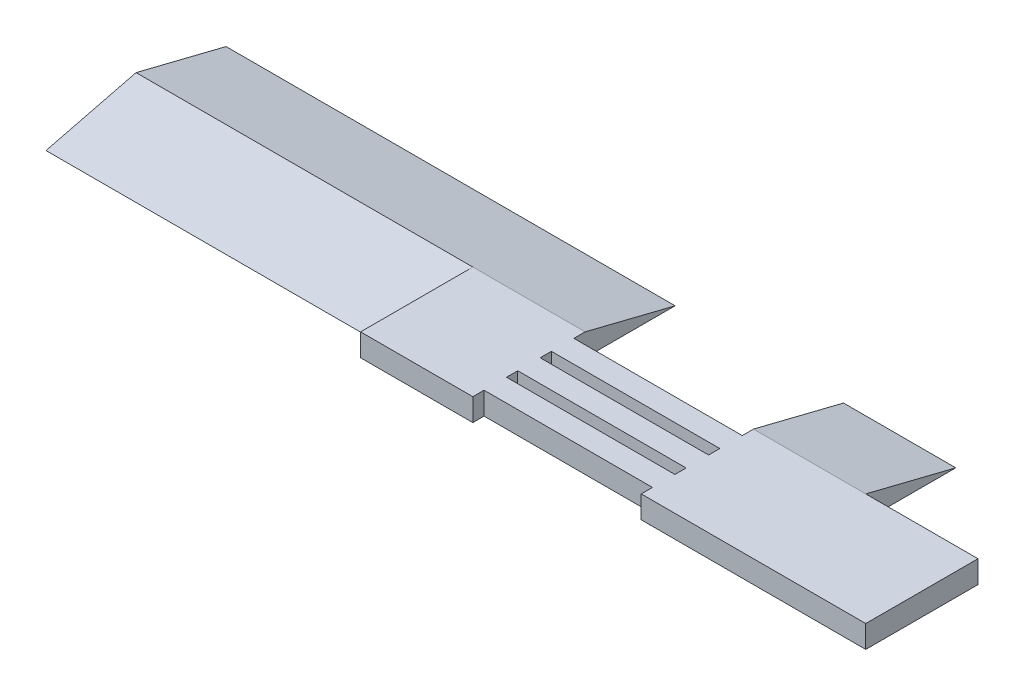
SolidWorks part; units mm, degrees
ref_plane "前视基准面" through (0, 0, 0) normal (0, 0, 1) x (1, 0, 0)
ref_plane "上视基准面" through (0, 0, 0) normal (0, 1, 0) x (1, 0, 0)
ref_plane "右视基准面" through (0, 0, 0) normal (1, 0, 0) x (0, 0, -1)
sketch "草图1" plane through (0, 0, 0) normal (0, 1, 0) x (1, 0, 0)
  line L1 (0, 0) -> (2000, 0)
  line L2 (0, 0) -> (0, 1000)
  line L3 (0, 1000) -> (2000, 1000)
  line L4 (2000, 0) -> (2000, 1000)
  dimension "D1" = 2000
  dimension "D2" = 1000
extrude "凸台-拉伸1" add sketch "草图1" along normal blind 200
sketch "草图2" plane through (0, 0, 0) normal (-1, 0, 0) x (0, 0, 1)
  line L0 (-1000, 200) -> (-1802.1562, 0)
  line L1 (-1000, 200) -> (-1000, 0) construction
  line L2 (-1000, 0) -> (-1802.1562, 0)
  line L3 (-1000, 200) -> (-1000, 0)
  dimension "D1" = 76
extrude "凸台-拉伸2" add sketch "草图2" against normal blind 1000
sketch "草图3" plane through (0, 0, 0) normal (-1, 0, 0) x (0, 0, 1)
  line L0 (-1000, 200) -> (0, 200) construction
  line L1 (-100, 200) -> (-300, 200)
  line L2 (-100, 200) -> (-100, 0)
  line L3 (-100, 0) -> (-300, 0)
  line L4 (-300, 200) -> (-300, 0)
  line L5 (-1802.1562, 0) -> (0, 0) construction
  line L6 (0, 200) -> (0, 0) construction
  line L7 (-400, 200) -> (-600, 200)
  line L8 (-400, 200) -> (-400, 0)
  line L9 (-400, 0) -> (-600, 0)
  line L10 (-600, 200) -> (-600, 0)
  line L11 (-700, 200) -> (-900, 200)
  line L12 (-700, 200) -> (-700, 0)
  line L13 (-700, 0) -> (-900, 0)
  line L14 (-900, 200) -> (-900, 0)
  dimension "D1" = 100
  dimension "D2" = 100
  dimension "D3" = 200
  dimension "D4" = 200
  dimension "D5" = 200
  dimension "D6" = 100
extrude "凸台-拉伸3" add sketch "草图3" along normal blind 1500
sketch "草图4" plane through (0, 0, 0) normal (0, 1, 0) x (1, 0, 0)
  line L0 (0, 0) -> (2000, 0) construction
  line L1 (-1500, 1000) -> (-2500, 1000)
  line L2 (-1500, 1000) -> (-1500, 0)
  line L3 (-1500, 0) -> (-2500, 0)
  line L4 (-2500, 1000) -> (-2500, 0)
  line L5 (-1500, 700) -> (-1500, 900) construction
  dimension "D1" = 1000
  dimension "D2" = 1000
extrude "凸台-拉伸4" add sketch "草图4" along normal blind 200
sketch "草图5" plane through (-1500, 0, 0) normal (1, 0, 0) x (0, 0, -1)
  line L0 (1802.1562, 0) -> (1000, 0) construction
  line L1 (1000, 200) -> (1802.1562, 0) construction
  line L2 (1802.1562, 0) -> (197.8438, 0)
  line L3 (1000, 200) -> (1802.1562, 0)
  line L4 (1000, 200) -> (1000, 0) construction
  line L5 (1000, 200) -> (197.8438, 0)
extrude "凸台-拉伸5" add sketch "草图5" against normal blind 4000
